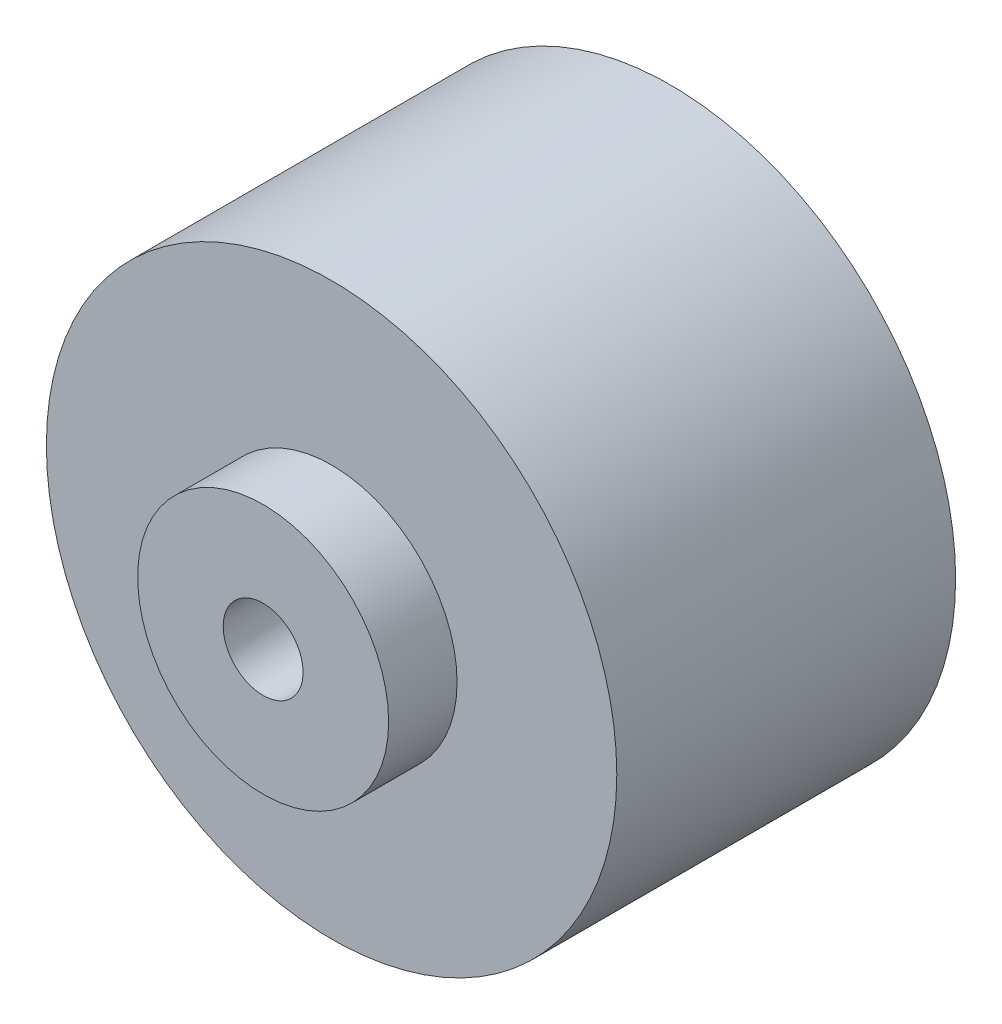
SolidWorks part; units mm, degrees
ref_plane "Ön Düzlem" through (0, 0, 0) normal (0, 0, 1) x (1, 0, 0)
ref_plane "Üst Düzlem" through (0, 0, 0) normal (0, 1, 0) x (1, 0, 0)
ref_plane "Sağ Düzlem" through (0, 0, 0) normal (1, 0, 0) x (0, 0, -1)
sketch "Sketch1" plane through (0, 0, 0) normal (0, 0, 1) x (1, 0, 0)
  circle A0 centre (0, 0) radius 25
  dimension "D1" = 50
extrude "Boss-Extrude1" add sketch "Sketch1" along normal blind 29.7
sketch "Sketch2" plane through (0, 0, 29.7) normal (0, 0, 1) x (1, 0, 0)
  circle A0 centre (0, 0) radius 11
  dimension "D1" = 22
extrude "Boss-Extrude2" add sketch "Sketch2" along normal blind 6
sketch "Sketch3" plane through (0, 0, 0) normal (0, 0, -1) x (-1, 0, 0)
  circle A0 centre (0, 0) radius 12.25
  dimension "D1" = 24.5
extrude "Boss-Extrude3" add sketch "Sketch3" along normal blind 9
sketch "Sketch4" plane through (0, 0, -9) normal (0, 0, -1) x (-1, 0, 0)
  circle A0 centre (0, 0) radius 3.5
extrude "Cut-Extrude1" cut sketch "Sketch4" against normal through all
